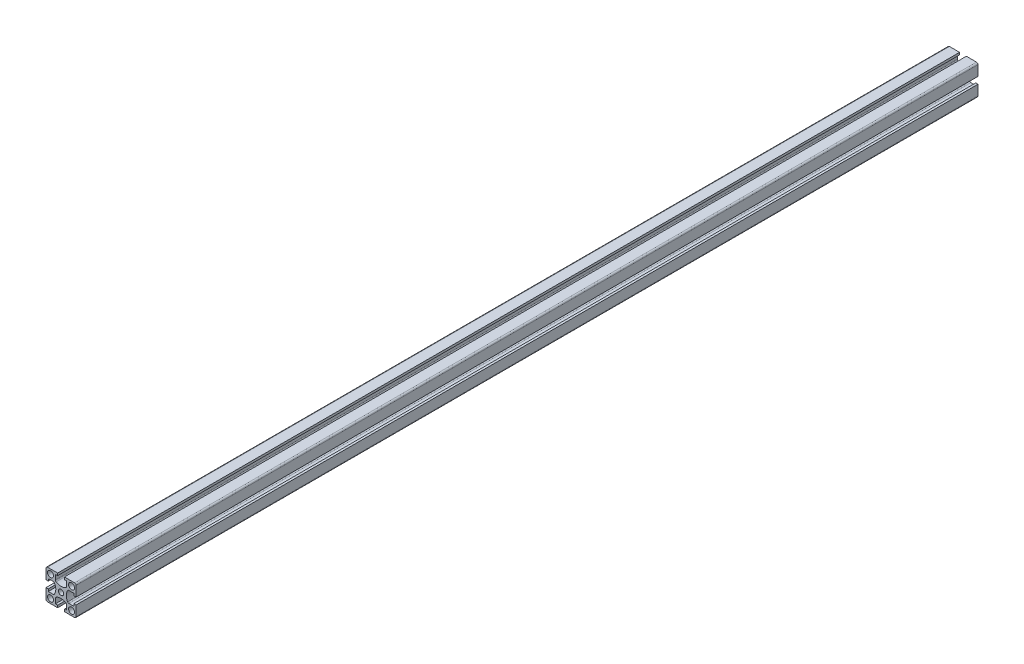
SolidWorks part; units mm, degrees
ref_plane "Front Plane" through (0, 0, 0) normal (0, 0, 1) x (1, 0, 0)
ref_plane "Top Plane" through (0, 0, 0) normal (0, 1, 0) x (1, 0, 0)
ref_plane "Right Plane" through (0, 0, 0) normal (1, 0, 0) x (0, 0, -1)
sketch "Sketch1" plane through (0, 0, 0) normal (0, 0, 1) x (1, 0, 0)
  line L64 (-10, 9) -> (-10, 2.25)
  line L65 (-10, 2.25) -> (-8.5, 2.25)
  line L66 (-8.5, 2.25) -> (-8.5, 3.75)
  line L67 (-8.5, 3.75) -> (-5.2369, 3.75)
  line L68 (-5.2369, -3.75) -> (-8.5, -3.75)
  line L69 (-8.5, -3.75) -> (-8.5, -2.25)
  line L70 (-8.5, -2.25) -> (-10, -2.25)
  line L71 (-10, -2.25) -> (-10, -9)
  line L72 (-9, -10) -> (-2.25, -10)
  line L73 (-2.25, -10) -> (-2.25, -8.5)
  line L74 (-2.25, -8.5) -> (-3.75, -8.5)
  line L75 (-3.75, -8.5) -> (-3.75, -5.2369)
  line L76 (3.75, -5.2369) -> (3.75, -8.5)
  line L77 (3.75, -8.5) -> (2.25, -8.5)
  line L78 (2.25, -8.5) -> (2.25, -10)
  line L79 (2.25, -10) -> (9, -10)
  line L80 (10, -9) -> (10, -2.25)
  line L81 (10, -2.25) -> (8.5, -2.25)
  line L82 (8.5, -2.25) -> (8.5, -3.75)
  line L83 (8.5, -3.75) -> (5.2369, -3.75)
  line L84 (5.2369, 3.75) -> (8.5, 3.75)
  line L85 (8.5, 3.75) -> (8.5, 2.25)
  line L86 (8.5, 2.25) -> (10, 2.25)
  line L87 (10, 2.25) -> (10, 9)
  line L88 (9, 10) -> (2.25, 10)
  line L89 (2.25, 10) -> (2.25, 8.5)
  line L90 (2.25, 8.5) -> (3.75, 8.5)
  line L91 (3.75, 8.5) -> (3.75, 5.2369)
  line L92 (-3.75, 5.2369) -> (-3.75, 8.5)
  line L93 (-3.75, 8.5) -> (-2.25, 8.5)
  line L94 (-2.25, 8.5) -> (-2.25, 10)
  line L95 (-2.25, 10) -> (-9, 10)
  circle A5 centre (-7, -7) radius 2
  circle A6 centre (7, -7) radius 2
  circle A7 centre (7, 7) radius 2
  circle A8 centre (0, 0) radius 1.75
  circle A9 centre (-7, 7) radius 2
  arc A32 (-9, 10) -> (-10, 9) centre (-9, 9) ccw
  arc A33 (-4.3708, 3.25) -> (-5.2369, 3.75) centre (-5.2369, 2.75) ccw
  arc A34 (-4.3708, -3.25) -> (-4.3708, 3.25) centre (-10, 0) ccw
  arc A35 (-5.2369, -3.75) -> (-4.3708, -3.25) centre (-5.2369, -2.75) ccw
  arc A36 (-10, -9) -> (-9, -10) centre (-9, -9) ccw
  arc A37 (-3.25, -4.3708) -> (-3.75, -5.2369) centre (-2.75, -5.2369) ccw
  arc A38 (3.25, -4.3708) -> (-3.25, -4.3708) centre (0, -10) ccw
  arc A39 (3.75, -5.2369) -> (3.25, -4.3708) centre (2.75, -5.2369) ccw
  arc A40 (9, -10) -> (10, -9) centre (9, -9) ccw
  arc A41 (4.3708, -3.25) -> (5.2369, -3.75) centre (5.2369, -2.75) ccw
  arc A42 (4.3708, 3.25) -> (4.3708, -3.25) centre (10, 0) ccw
  arc A43 (5.2369, 3.75) -> (4.3708, 3.25) centre (5.2369, 2.75) ccw
  arc A44 (10, 9) -> (9, 10) centre (9, 9) ccw
  arc A45 (3.25, 4.3708) -> (3.75, 5.2369) centre (2.75, 5.2369) ccw
  arc A46 (-3.25, 4.3708) -> (3.25, 4.3708) centre (0, 10) ccw
  arc A47 (-3.75, 5.2369) -> (-3.25, 4.3708) centre (-2.75, 5.2369) ccw
extrude "Boss-Extrude1" add sketch "Sketch1" along normal blind 600
